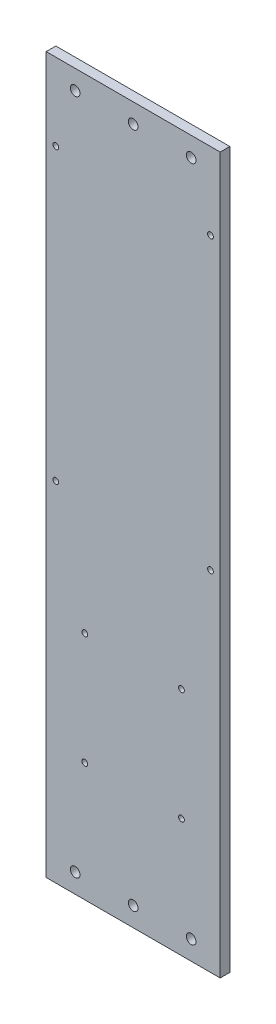
SolidWorks part; units mm, degrees
ref_plane "前视基准面" through (0, 0, 0) normal (0, 0, 1) x (1, 0, 0)
ref_plane "上视基准面" through (0, 0, 0) normal (0, 1, 0) x (1, 0, 0)
ref_plane "右视基准面" through (0, 0, 0) normal (1, 0, 0) x (0, 0, -1)
sketch "草图2" plane through (0, 0, 0) normal (0, 0, 1) x (1, 0, 0)
  line L1 (45, -185) -> (-45, -185)
  line L2 (45, -185) -> (45, 185)
  line L3 (45, 185) -> (-45, 185)
  line L4 (-45, -185) -> (-45, 185)
  line L5 (45, -185) -> (-45, 185) construction
  line L6 (45, 185) -> (-45, -185) construction
  point P0 (0, 0)
  dimension "D1" = 370
  dimension "D2" = 90
extrude "凸台-拉伸1" add sketch "草图2" along normal mid plane 5
sketch "草图3" plane through (0, 0, 2.5) normal (0, 0, 1) x (1, 0, 0)
  line L0 (0, 185) -> (0, 175) construction
  line L1 (45, 185) -> (-45, 185) construction
  line L2 (0, 0) -> (45, 0) construction
  line L3 (45, -185) -> (45, 185) construction
  line L4 (0, -185) -> (0, -175) construction
  circle A0 centre (0, 175) radius 2.5
  circle A1 centre (30, 175) radius 2.5
  circle A2 centre (-30, 175) radius 2.5
  circle A3 centre (-30, -175) radius 2.5
  circle A4 centre (30, -175) radius 2.5
  circle A5 centre (0, -175) radius 2.5
  dimension "D1" = 5
  dimension "D2" = 10
  dimension "D3" = 2
  dimension "D4" = 2
extrude "切除-拉伸1" cut sketch "草图3" against normal through all
sketch "草图5" plane through (0, 0, 2.5) normal (0, 0, 1) x (1, 0, 0)
  line L0 (0, 70.1728) -> (0, 66.4415) construction
  line L1 (0, 145.1728) -> (0, 70.1728) construction
  line L2 (0, 145.1728) -> (40, 145.1728) construction
  line L3 (0, 70.1728) -> (32.6102, 70.1728) construction
  line L4 (0, -4.8272) -> (40, -4.8272) construction
  circle A0 centre (40, 145.1728) radius 1.5
  circle A1 centre (-40, 145.1728) radius 1.5
  circle A2 centre (-40, -4.8272) radius 1.5
  circle A3 centre (40, -4.8272) radius 1.5
  dimension "D1" = 3
  dimension "D2" = 40
  dimension "D3" = 75
extrude "切除-拉伸3" cut sketch "草图5" against normal through all
sketch "草图6" plane through (0, 0, 2.5) normal (0, 0, 1) x (1, 0, 0)
  line L0 (0, -94.576) -> (0, -123.576) construction
  line L1 (0, -94.576) -> (29.0518, -94.576) construction
  line L2 (0, -123.576) -> (25, -123.576) construction
  circle A0 centre (25, -123.576) radius 1.5
  circle A1 centre (-25, -123.576) radius 1.5
  circle A2 centre (25, -65.576) radius 1.5
  circle A3 centre (-25, -65.576) radius 1.5
  dimension "D1" = 3
  dimension "D2" = 25
  dimension "D3" = 29
extrude "切除-拉伸4" cut sketch "草图6" against normal through all
